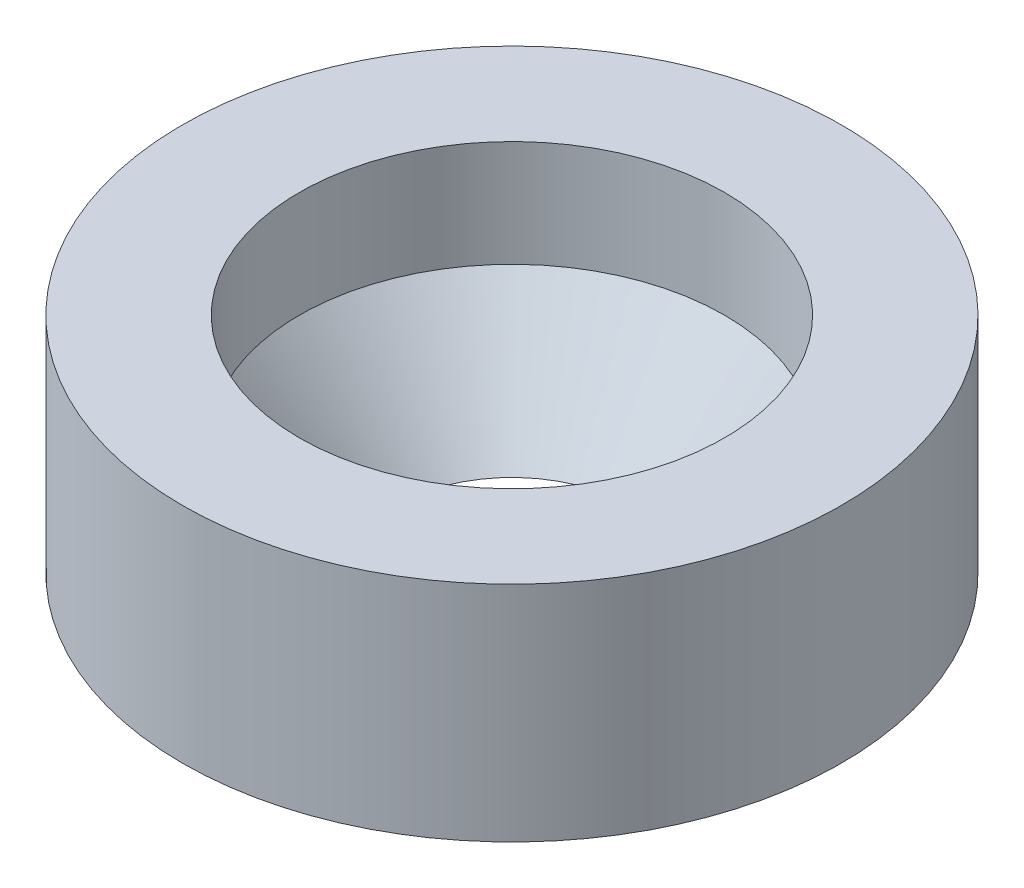
SolidWorks part; units mm, degrees
ref_plane "Front Plane" through (0, 0, 0) normal (0, 0, 1) x (1, 0, 0)
ref_plane "Top Plane" through (0, 0, 0) normal (0, 1, 0) x (1, 0, 0)
ref_plane "Right Plane" through (0, 0, 0) normal (1, 0, 0) x (0, 0, -1)
sketch "Sketch1" plane through (0, 0, 0) normal (1, 0, 0) x (0, 0, -1)
  line L0 (0, 0) -> (2.2, 0) construction
  line L1 (2.2, 0) -> (6.2, 0)
  line L2 (6.2, 0) -> (6.2, 2.2)
  line L3 (6.2, 2.2) -> (4, 2.2)
  line L4 (4, 2.2) -> (2.2, 0)
  line L5 (4, 2.2) -> (0, 2.2) construction
  line L6 (0, 2.2) -> (0, 0) construction
  line L8 (4, 2.2) -> (6.2, 2.2)
  line L9 (4, 2.2) -> (4, 4.2)
  line L10 (4, 4.2) -> (6.2, 4.2)
  line L11 (6.2, 2.2) -> (6.2, 4.2)
  dimension "D1" = 2.2
  dimension "D2" = 4
  dimension "D3" = 4
  dimension "D4" = 2.2
  dimension "D5" = 2
revolve "Revolve1" add sketch "Sketch1" angle 360 about L6
